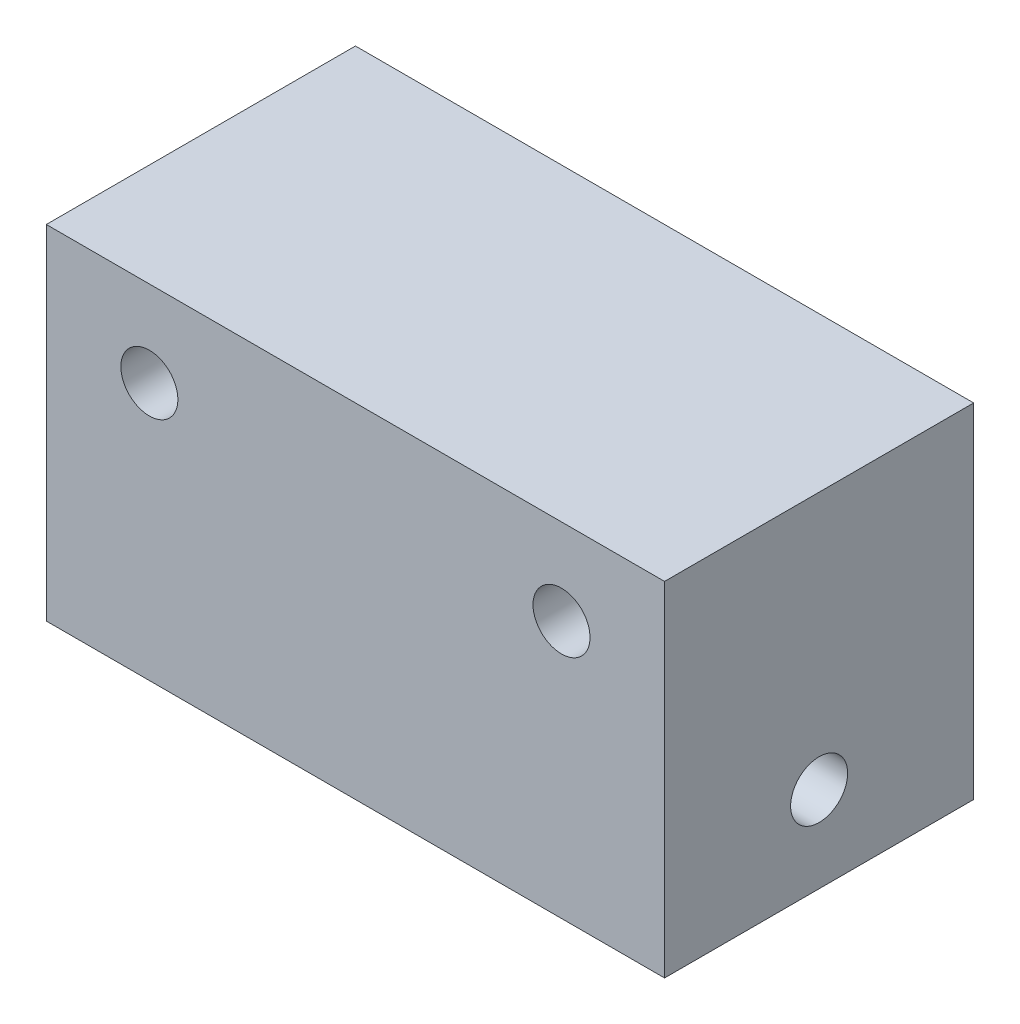
SolidWorks part; units mm, degrees
ref_plane "前视基准面" through (0, 0, 0) normal (0, 0, 1) x (1, 0, 0)
ref_plane "上视基准面" through (0, 0, 0) normal (0, 1, 0) x (1, 0, 0)
ref_plane "右视基准面" through (0, 0, 0) normal (1, 0, 0) x (0, 0, -1)
sketch "Sketch1" plane through (0, 0, 0) normal (0, 1, 0) x (1, 0, 0)
  line L1 (-45, 22.5) -> (45, 22.5)
  line L2 (-45, 22.5) -> (-45, -22.5)
  line L3 (-45, -22.5) -> (45, -22.5)
  line L4 (45, 22.5) -> (45, -22.5)
  line L5 (-45, 22.5) -> (45, -22.5) construction
  line L6 (-45, -22.5) -> (45, 22.5) construction
  point P0 (0, 0)
  dimension "D1" = 90
  dimension "D2" = 45
extrude "Boss-Extrude1" add sketch "Sketch1" along normal blind 50
sketch "Sketch2" plane through (0, 0, 22.5) normal (0, 0, 1) x (1, 0, 0)
  line L0 (-45, 25) -> (45, 25) construction
  line L1 (-45, 50) -> (-45, 0) construction
  line L2 (45, 50) -> (45, 0) construction
  line L3 (-45, 50) -> (45, 50) construction
  line L4 (0, -6.1777) -> (0, 0) construction
  circle A0 centre (-30, 37.5) radius 4.15
  circle A1 centre (30, 37.5) radius 4.15
  dimension "D1" = 8.3
  dimension "D2" = 30
  dimension "D3" = 12.5
extrude "Cut-Extrude1" cut sketch "Sketch2" against normal blind 28.2967
sketch "Sketch3" plane through (45, 0, 0) normal (1, 0, 0) x (0, 0, -1)
  line L0 (-22.5, 0) -> (22.5, 0) construction
  circle A0 centre (0, 12.5) radius 4.15
  dimension "D1" = 12.5
  dimension "D2" = 8.3
extrude "Cut-Extrude2" cut sketch "Sketch3" against normal through all
sketch "Sketch4" plane through (0, 50, 0) normal (0, 1, 0) x (1, 0, 0)
  line L0 (-45, -22.5) -> (45, -22.5) construction
  circle A0 centre (-23.1091, -7.5) radius 1.5
  circle A1 centre (-23.1091, 7.5) radius 1.5
  dimension "D1" = 3
  dimension "D2" = 15
  dimension "D3" = 3
  dimension "D4" = 15
